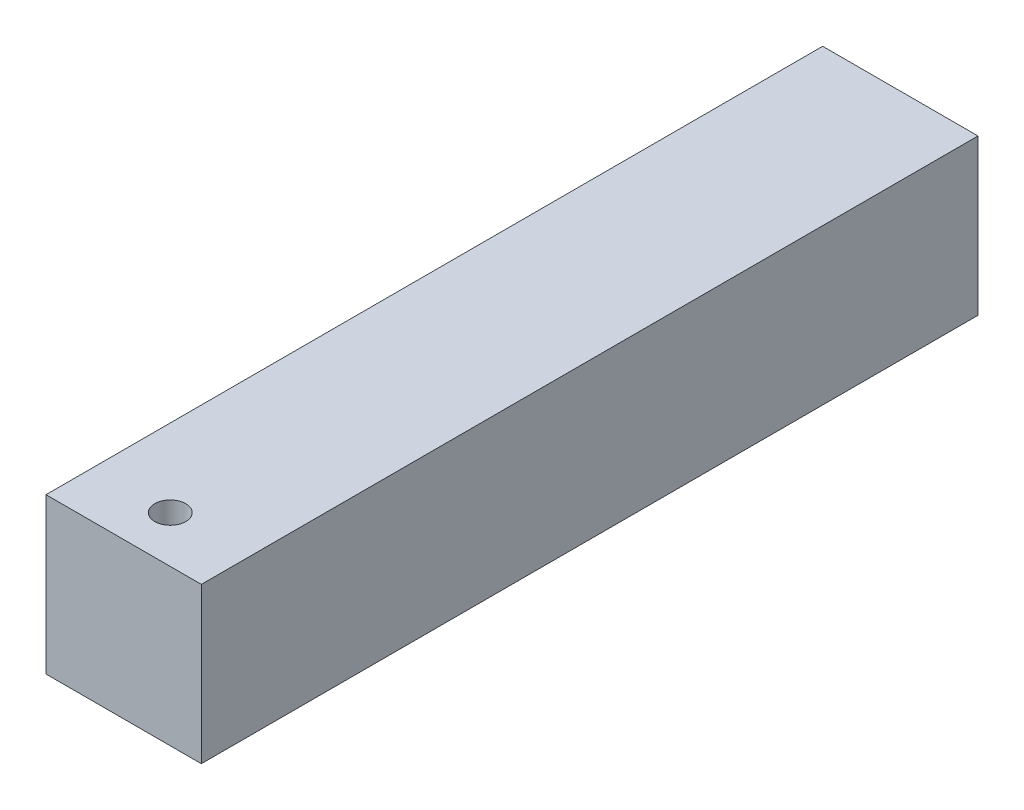
SolidWorks part; units mm, degrees
ref_plane "Front Plane" through (0, 0, 0) normal (0, 0, 1) x (1, 0, 0)
ref_plane "Top Plane" through (0, 0, 0) normal (0, 1, 0) x (1, 0, 0)
ref_plane "Right Plane" through (0, 0, 0) normal (1, 0, 0) x (0, 0, -1)
sketch "Sketch1" plane through (0, 0, 0) normal (0, 0, 1) x (1, 0, 0)
  line L1 (0, 0) -> (10, 0)
  line L2 (0, 0) -> (0, -10)
  line L3 (0, -10) -> (10, -10)
  line L4 (10, 0) -> (10, -10)
  dimension "D1" = 10
  dimension "D2" = 10
extrude "Boss-Extrude1" add sketch "Sketch1" along normal blind 50
sketch "Sketch2" plane through (0, -10, 0) normal (0, -1, 0) x (-1, 0, 0)
  line L0 (0, -50) -> (-10, -50) construction
  circle A0 centre (-5, -47) radius 1
  point P4 (0, 0)
  point P5 (-5, -50)
  dimension "D1" = 2
  dimension "D2" = 3
extrude "Cut-Extrude1" cut sketch "Sketch2" against normal blind 50
